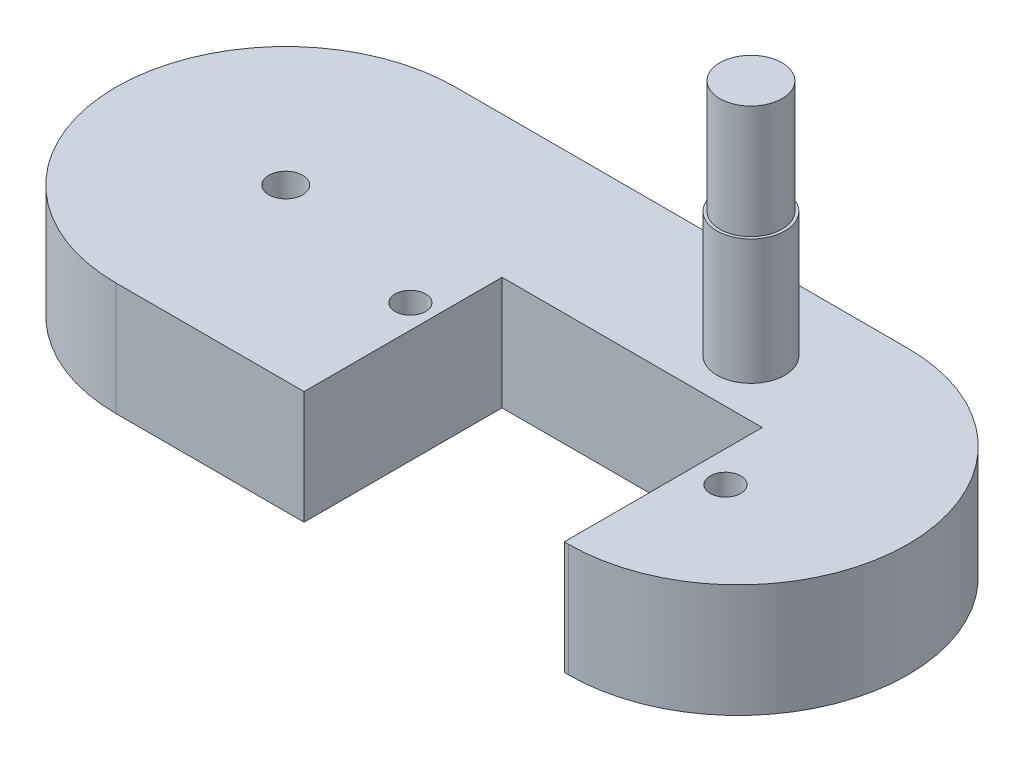
SolidWorks part; units mm, degrees
ref_plane "Front Plane" through (0, 0, 0) normal (0, 0, 1) x (1, 0, 0)
ref_plane "Top Plane" through (0, 0, 0) normal (0, 1, 0) x (1, 0, 0)
ref_plane "Right Plane" through (0, 0, 0) normal (1, 0, 0) x (0, 0, -1)
sketch "Sketch2" plane through (0, 0, 0) normal (0, 1, 0) x (1, 0, 0)
  line L0 (0, 0) -> (40, 0) construction
  line L1 (0, 15) -> (40, 15)
  line L2 (0, -15) -> (16.6203, -15)
  line L3 (16.6203, -10) -> (16.6203, -15)
  line L4 (16.6203, 2.5) -> (39.6203, 2.5)
  line L5 (16.6203, 2.5) -> (16.6203, -10)
  line L7 (39.6203, 2.5) -> (39.6203, -10)
  line L8 (39.6203, -10) -> (39.6203, -15)
  line L9 (39.6203, -15) -> (40, -15)
  arc A0 (0, 15) -> (0, -15) centre (0, 0) ccw
  arc A1 (40, -15) -> (40, 15) centre (40, 0) ccw
  circle A2 centre (0, 0) radius 1.5
  circle A3 centre (42.3703, -3.5) radius 1.35
  circle A4 centre (14.5203, -3.5) radius 1.35
  point P3 (20, 0)
  dimension "D1" = 3
  dimension "D2" = 15
  dimension "D4" = 23
  dimension "D5" = 12.5
  dimension "D6" = 2.75
  dimension "D7" = 2.7
  dimension "D8" = 2.7
  dimension "D3" = 40
  dimension "D9" = 2.1
  dimension "D10" = 6
extrude "Boss-Extrude5" add sketch "Sketch2" along normal blind 10
sketch "Sketch6" plane through (0, 10, 0) normal (0, 1, 0) x (1, 0, 0)
  line L0 (16.6203, 2.5) -> (39.6203, 2.5) construction
  line L1 (39.6203, 2.5) -> (39.6203, -15) construction
  circle A0 centre (33.6203, 7.5) radius 3
  point P6 (0, 0)
  dimension "D1" = 6
  dimension "D2" = 5
  dimension "D3" = 6
extrude "Boss-Extrude11" add sketch "Sketch6" along normal blind 24.05
sketch "Sketch12" plane through (0, 34.05, 0) normal (0, 1, 0) x (1, 0, 0)
  circle A0 centre (33.6203, 7.5) radius 2.75
  dimension "D1" = 5.5
extrude "Cut-Extrude10" cut sketch "Sketch12" against normal blind 13 flip side to cut
sketch "Sketch13" plane through (0, 34.05, 0) normal (0, 1, 0) x (1, 0, 0)
  circle A0 centre (33.6203, 7.5) radius 2.75
  dimension "D1" = 5.5
extrude "Cut-Extrude11" cut sketch "Sketch13" against normal blind 3
